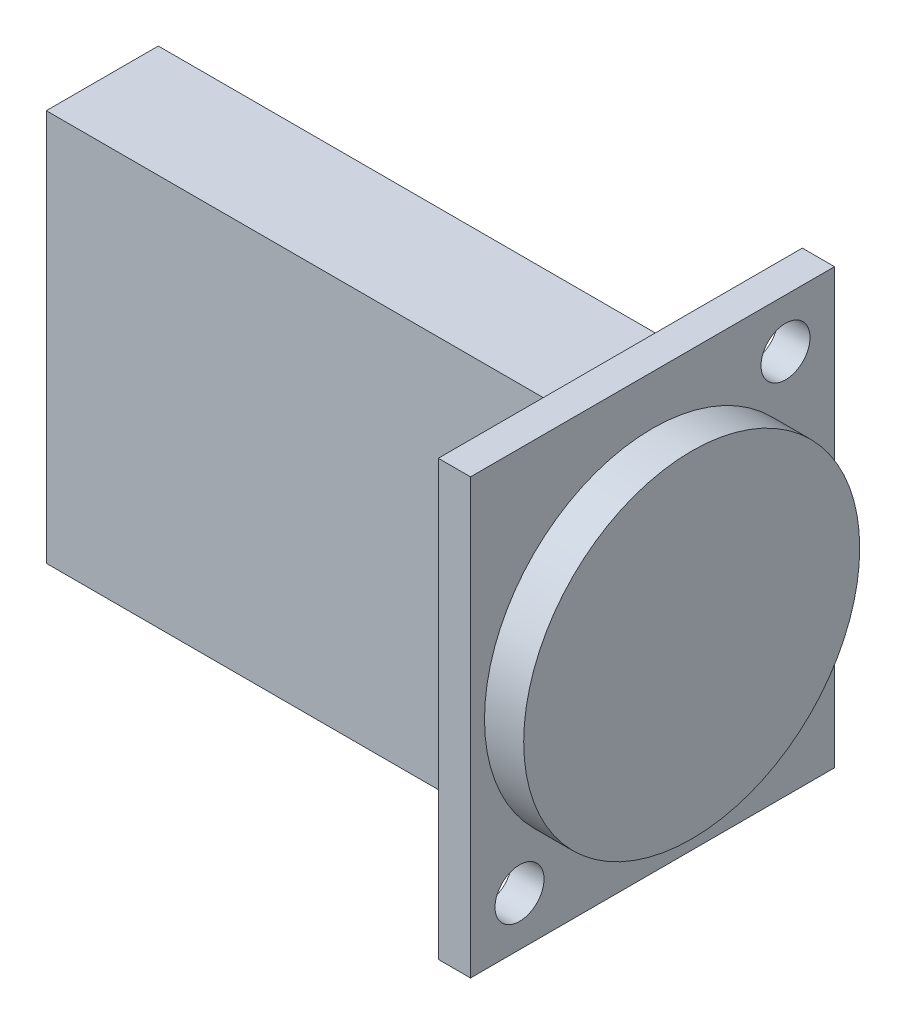
SolidWorks part; units mm, degrees
ref_plane "Front Plane" through (0, 0, 0) normal (0, 0, 1) x (1, 0, 0)
ref_plane "Top Plane" through (0, 0, 0) normal (0, 1, 0) x (1, 0, 0)
ref_plane "Right Plane" through (0, 0, 0) normal (1, 0, 0) x (0, 0, -1)
sketch "Sketch2" plane through (0, 0, 0) normal (1, 0, 0) x (0, 0, -1)
  line L1 (13, -15.5) -> (-13, -15.5)
  line L2 (13, -15.5) -> (13, 15.5)
  line L3 (13, 15.5) -> (-13, 15.5)
  line L4 (-13, -15.5) -> (-13, 15.5)
  line L5 (13, -15.5) -> (-13, 15.5) construction
  line L6 (13, 15.5) -> (-13, -15.5) construction
  circle A0 centre (-9.5, -12) radius 1.75
  circle A1 centre (9.5, 12) radius 1.75
  point P0 (0, 0)
  point P10 (11, 12)
  dimension "D7" = 3.5
  dimension "D1" = 31
  dimension "D2" = 26
  dimension "D3" = 19
  dimension "D4" = 9.5
  dimension "D5" = 24
  dimension "D6" = 12
extrude "Boss-Extrude1" add sketch "Sketch2" along normal blind 2.3
sketch "Sketch3" plane through (2.3, 0, 0) normal (1, 0, 0) x (0, 0, -1)
  circle A0 centre (0, 0) radius 12
  dimension "D1" = 24
extrude "Boss-Extrude2" add sketch "Sketch3" along normal blind 2.8
sketch "Sketch4" plane through (0, 0, 0) normal (-1, 0, 0) x (0, 0, 1)
  line L1 (4, -14) -> (-4, -14)
  line L2 (4, -14) -> (4, 14)
  line L3 (4, 14) -> (-4, 14)
  line L4 (-4, -14) -> (-4, 14)
  line L5 (4, -14) -> (-4, 14) construction
  line L6 (4, 14) -> (-4, -14) construction
  point P0 (0, 0)
  dimension "D1" = 28
  dimension "D2" = 8
extrude "Boss-Extrude3" add sketch "Sketch4" along normal blind 37
